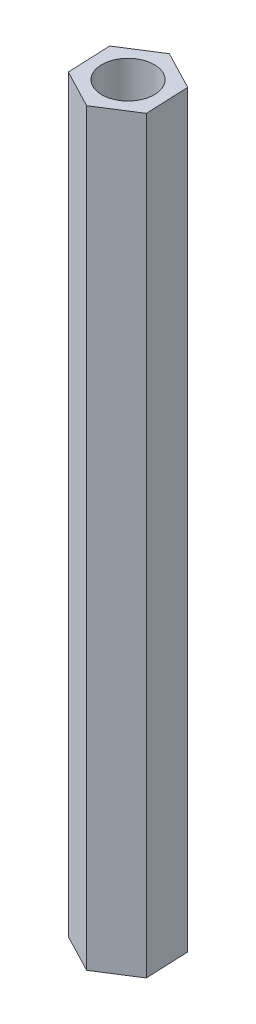
SolidWorks part; units mm, degrees
ref_plane "前视基准面" through (0, 0, 0) normal (0, 0, 1) x (1, 0, 0)
ref_plane "上视基准面" through (0, 0, 0) normal (0, 1, 0) x (1, 0, 0)
ref_plane "右视基准面" through (0, 0, 0) normal (1, 0, 0) x (0, 0, -1)
other "Configuration Table"
sketch "草图1" plane through (0, 0, 0) normal (0, 1, 0) x (1, 0, 0)
  line L1 (3.0707, -1.6034) -> (2.9239, 1.8576)
  line L2 (2.9239, 1.8576) -> (-0.1468, 3.461)
  line L3 (-0.1468, 3.461) -> (-3.0707, 1.6034)
  line L4 (-3.0707, 1.6034) -> (-2.9239, -1.8576)
  line L5 (-2.9239, -1.8576) -> (0.1468, -3.461)
  line L6 (0.1468, -3.461) -> (3.0707, -1.6034)
  circle A0 centre (0, 0) radius 2.1
  circle A1 centre (0, 0) radius 3 construction
extrude "凸台-拉伸1" add sketch "草图1" along normal blind 60
